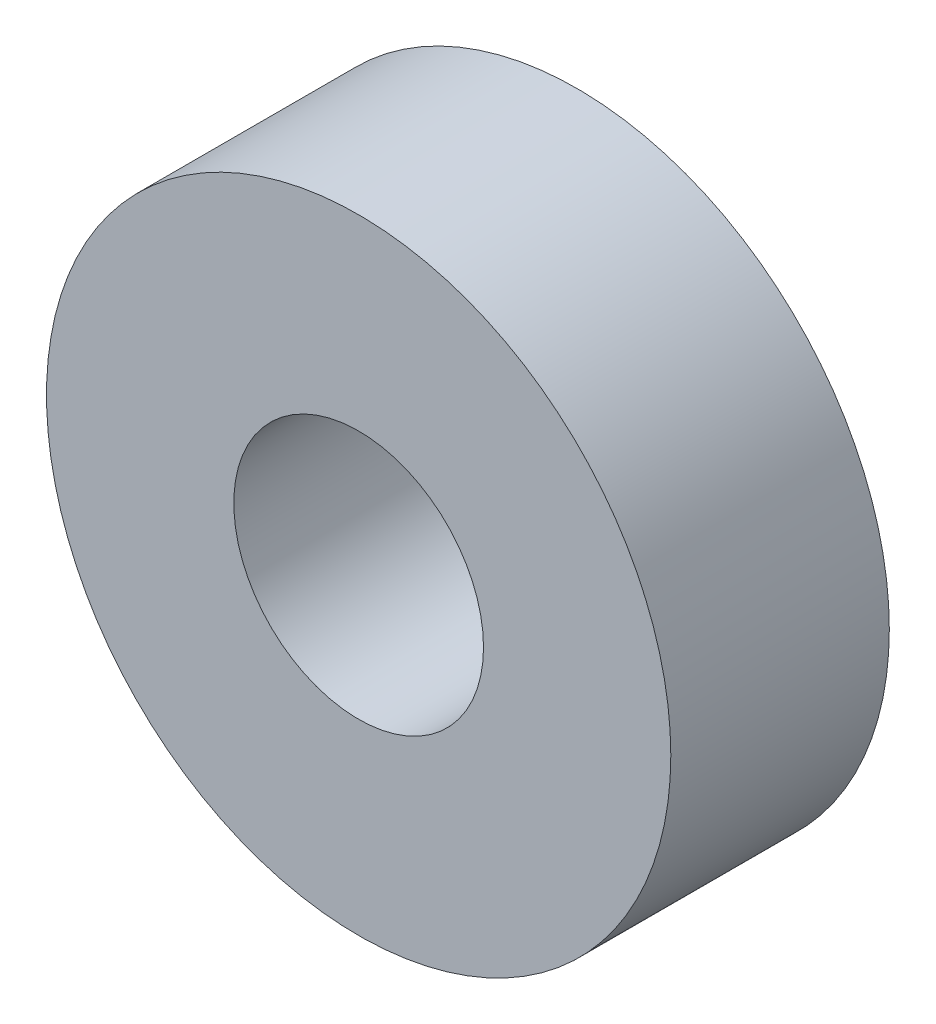
SolidWorks part; units mm, degrees
material "Alloy Steel"
ref_plane "Front Plane" through (0, 0, 0) normal (0, 0, 1) x (1, 0, 0)
ref_plane "Top Plane" through (0, 0, 0) normal (0, 1, 0) x (1, 0, 0)
ref_plane "Right Plane" through (0, 0, 0) normal (1, 0, 0) x (0, 0, -1)
sketch "Sketch1" plane through (0, 0, 0) normal (0, 0, 1) x (1, 0, 0)
  circle A0 centre (0, 0) radius 4
  circle A1 centre (0, 0) radius 10
  dimension "D1" = 8
  dimension "D2" = 20
extrude "Boss-Extrude1" add sketch "Sketch1" along normal blind 7
